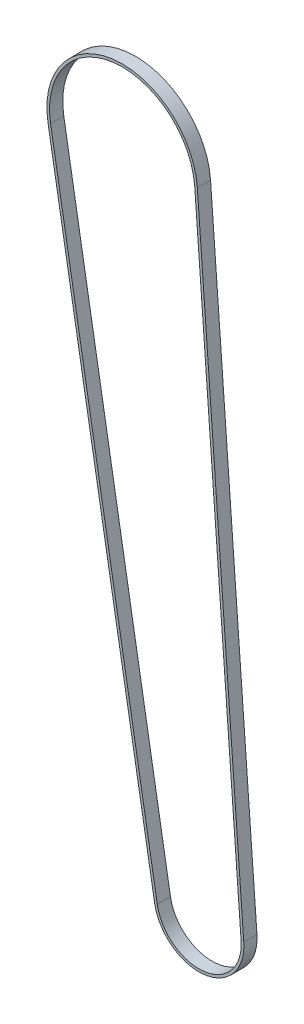
SolidWorks part; units mm, degrees
ref_plane "Front Plane" through (0, 0, 0) normal (0, 0, 1) x (1, 0, 0)
ref_plane "Top Plane" through (0, 0, 0) normal (0, 1, 0) x (1, 0, 0)
ref_plane "Right Plane" through (0, 0, 0) normal (1, 0, 0) x (0, 0, -1)
sketch "Sketch1" plane through (0, 0, 0) normal (0, 0, 1) x (1, 0, 0)
  line L0 (113.6921, 8.3725) -> (183.9011, -945.0058)
  line L1 (49.0612, -961.4825) -> (-112.3629, -19.2501)
  line L2 (109.7029, 8.0788) -> (179.9119, -945.2996)
  line L3 (53.0038, -960.8071) -> (-108.4204, -18.5747)
  arc A0 (-108.4204, -18.5747) -> (109.7029, 8.0788) centre (0, 0) cw
  arc A1 (179.9119, -945.2996) -> (53.0038, -960.8071) centre (116.0847, -950) cw
  arc A2 (-112.3629, -19.2501) -> (113.6921, 8.3725) centre (0, 0) cw
  arc A3 (183.9011, -945.0058) -> (49.0612, -961.4825) centre (116.0847, -950) cw
  dimension "D1" = 4
extrude "Boss-Extrude1" add sketch "Sketch1" along normal mid plane 20
